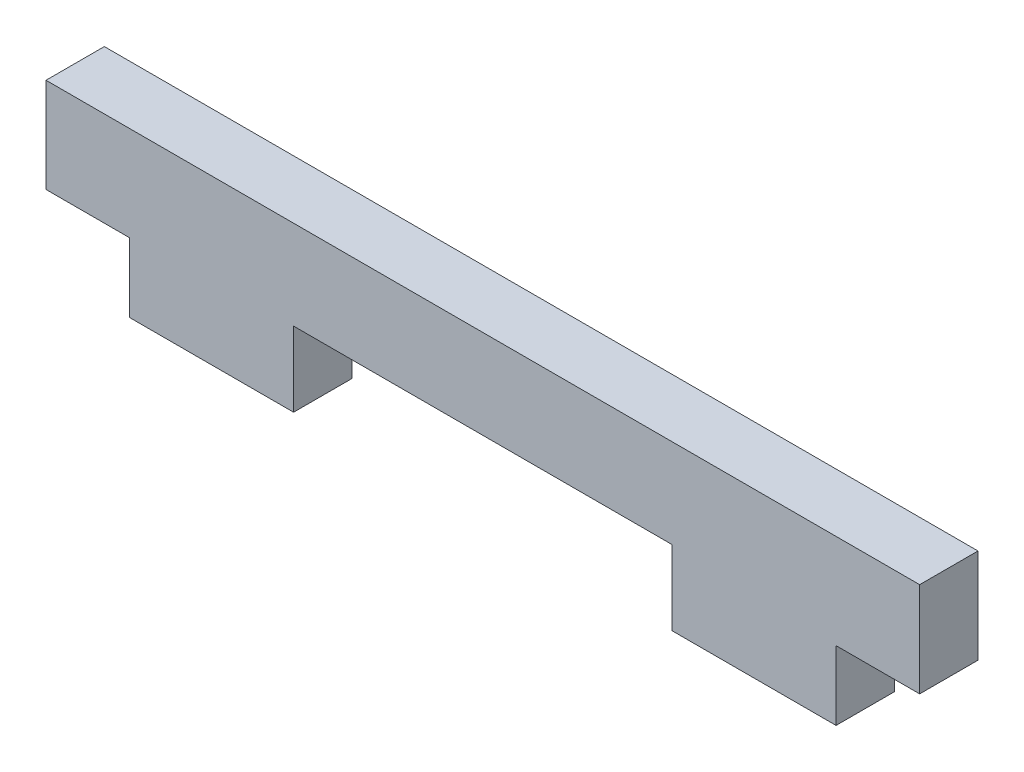
SolidWorks part; units mm, degrees
ref_plane "Front Plane" through (0, 0, 0) normal (0, 0, 1) x (1, 0, 0)
ref_plane "Top Plane" through (0, 0, 0) normal (0, 1, 0) x (1, 0, 0)
ref_plane "Right Plane" through (0, 0, 0) normal (1, 0, 0) x (0, 0, -1)
sketch "Sketch1" plane through (0, 0, 0) normal (0, 0, 1) x (1, 0, 0)
  line L0 (-21.6937, 0) -> (33.7063, 0)
  line L1 (33.7063, 0) -> (33.7063, -6)
  line L2 (33.7063, -6) -> (28.4063, -6)
  line L3 (28.4063, -6) -> (28.4063, -10.3818)
  line L4 (28.4063, -10.3818) -> (18.0063, -10.3818)
  line L5 (18.0063, -10.3818) -> (18.0063, -5.6501)
  line L6 (18.0063, -5.6501) -> (-5.9937, -5.6501)
  line L7 (-5.9937, -5.6501) -> (-5.9937, -10.3818)
  line L8 (-5.9937, -10.3818) -> (-16.3937, -10.3818)
  line L9 (-16.3937, -10.3818) -> (-16.3937, -6)
  line L10 (-16.3937, -6) -> (-21.6937, -6)
  line L11 (-21.6937, -6) -> (-21.6937, 0)
  dimension "D1" = 55.4
  dimension "D2" = 24
  dimension "D3" = 10.4
  dimension "D4" = 6
extrude "Boss-Extrude1" add sketch "Sketch1" along normal blind 3.7
